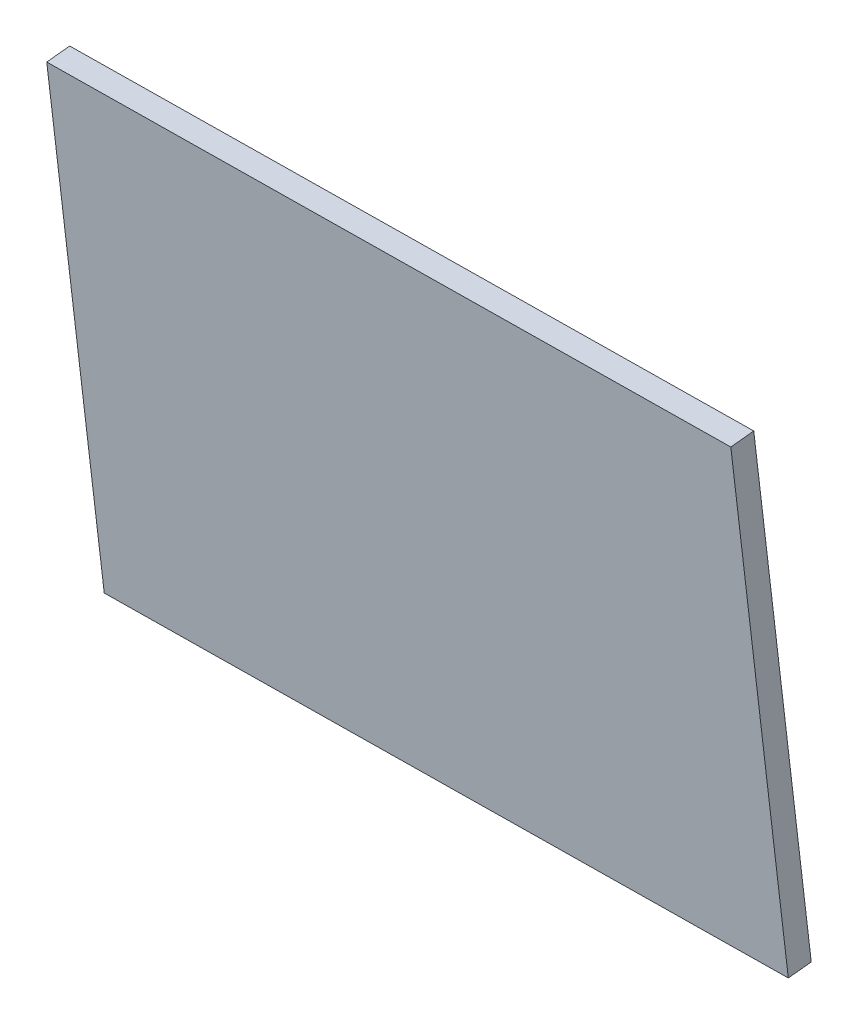
SolidWorks part; units mm, degrees
ref_plane "Front Plane" through (0, 0, 0) normal (0, 0, 1) x (1, 0, 0)
ref_plane "Top Plane" through (0, 0, 0) normal (0, 1, 0) x (1, 0, 0)
ref_plane "Right Plane" through (0, 0, 0) normal (1, 0, 0) x (0, 0, -1)
sketch "Sketch1" plane through (0, 22.0453, -209.7467) normal (0, 0.1045, -0.9945) x (-1, 0, 0)
  line L0 (-439.924, -699.3344) -> (-142.9538, -703.544)
  line L1 (-142.9538, -703.544) -> (-145.9304, -913.5229)
  line L2 (-145.9304, -913.5229) -> (-442.9005, -909.3133)
  line L3 (-442.9005, -909.3133) -> (-439.924, -699.3344)
  point P2 (0, 0)
  point P3 (0, 0)
  point P4 (0, 0)
  point P6 (0, 0)
  point P8 (-80.7724, -762.3434)
  point P9 (0, 0)
  point P10 (145.6045, -716.6378)
extrude "Boss-Extrude1" add sketch "Sketch1" against normal blind 10
